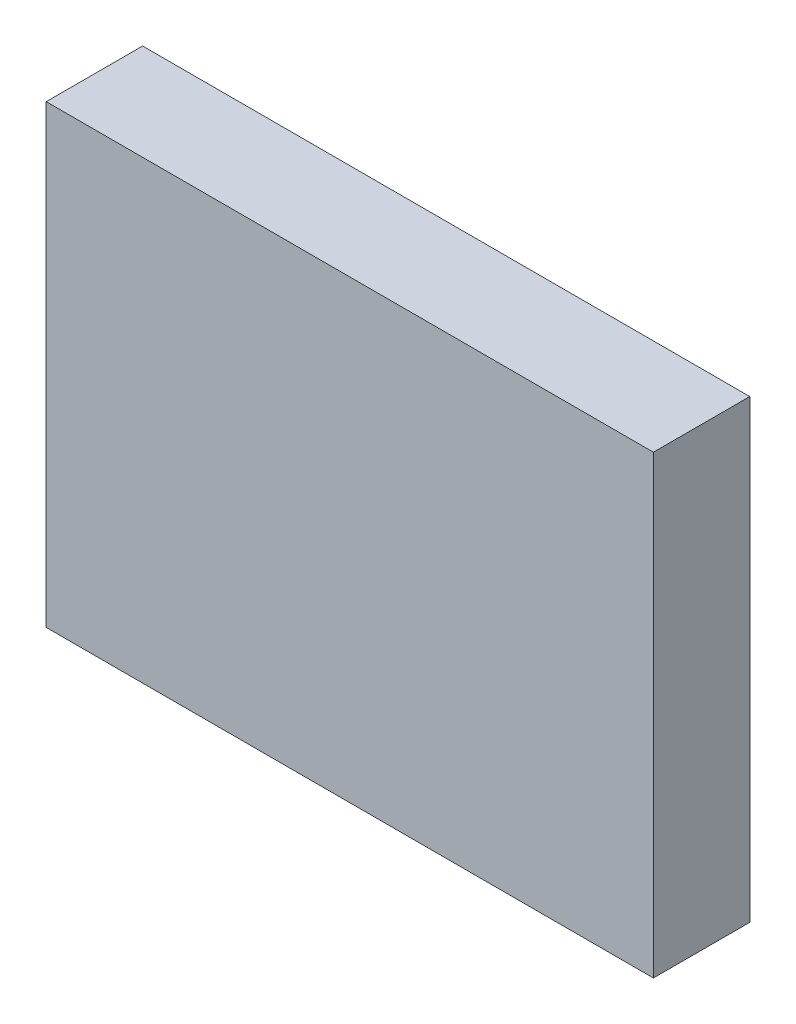
SolidWorks part; units mm, degrees
ref_plane "Front Plane" through (0, 0, 0) normal (0, 0, 1) x (1, 0, 0)
ref_plane "Top Plane" through (0, 0, 0) normal (0, 1, 0) x (1, 0, 0)
ref_plane "Right Plane" through (0, 0, 0) normal (1, 0, 0) x (0, 0, -1)
sketch "Sketch1" plane through (0, 0, 0) normal (0, 0, 1) x (1, 0, 0)
  line L1 (80, -60) -> (-80, -60)
  line L2 (80, -60) -> (80, 60)
  line L3 (80, 60) -> (-80, 60)
  line L4 (-80, -60) -> (-80, 60)
  line L5 (80, -60) -> (-80, 60) construction
  line L6 (80, 60) -> (-80, -60) construction
  point P0 (0, 0)
  dimension "D1" = 160
  dimension "D2" = 120
extrude "Boss-Extrude1" add sketch "Sketch1" along normal blind 25.4
